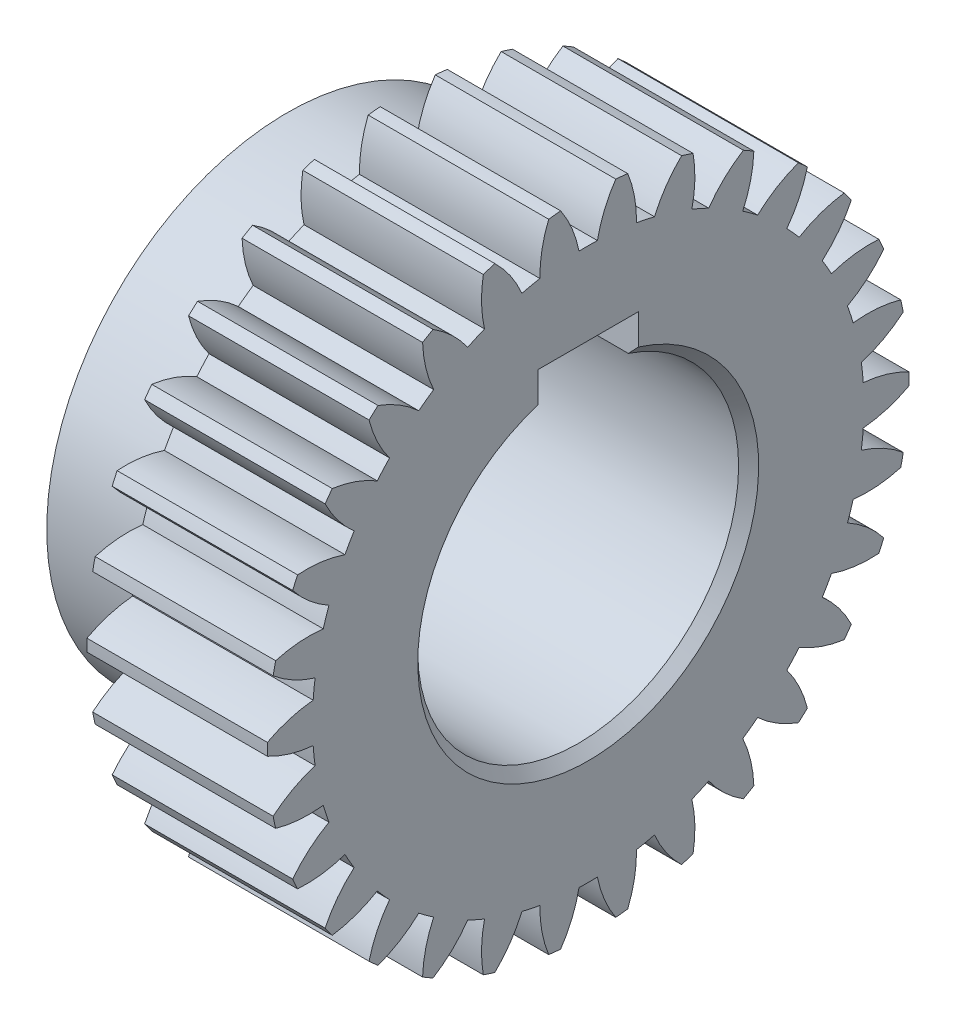
SolidWorks part; units mm, degrees
ref_plane "Plane1" through (0, 0, 0) normal (0, 0, 1) x (1, 0, 0)
ref_plane "Plane2" through (0, 0, 0) normal (0, 1, 0) x (1, 0, 0)
ref_plane "Plane3" through (0, 0, 0) normal (1, 0, 0) x (0, 0, -1)
sketch "HoldingSke" plane through (0, 0, 0) normal (0, 1, 0) x (1, 0, 0)
  line L0 (0, 0) -> (0.433, -0.25)
  line L1 (-15, 0) -> (100, 0) construction
  line L2 (0, 0) -> (-2.1039, 2.3779)
  line L3 (0, 0) -> (-11.863, 4.5341)
  line L4 (0, 0) -> (7.479, 4.318)
  line L5 (0, 0) -> (-28.1086, -10.4837)
  line L6 (0, 0) -> (-14.9213, -10.0675)
  line L7 (-2.1039, 2.3779) -> (4.3536, 31.6747)
  line L8 (-76.2, 54.61) -> (-72.9, 54.61)
  line L9 (-71.009, 38.7566) -> (-53.1078, 45.2721)
  line L10 (-76.2, 71.12) -> (104.1128, 71.12)
  line L11 (0, 0) -> (-18, 0)
  line L12 (-76.2, 101.6) -> (-76.133, 101.6)
  line L13 (24.9733, 27.94) -> (52.9518, 28.4284)
  line L14 (24.9733, 27.94) -> (24.9743, 27.94)
  line L15 (24.9733, 27.94) -> (100.4006, 29.5858)
  line L16 (-63.627, -2) -> (-12.827, -2)
  circle A0 centre (0, 0) radius 16
  circle A1 centre (0, 0) radius 24
  circle A2 centre (0, 0) radius 24
  circle A3 centre (0, 0) radius 16
  dimension "MHD" = 48
  dimension "Hub_dia" = 48
  dimension "Bore" = 32
  dimension "MBD" = 32
  dimension "Num_teeth" = 30
  dimension "Pitch" = 0.5
  dimension "Overall_len" = 30
  dimension "Show_teeth" = 30
  dimension "Thickness" = 18
  dimension "OAL" = 30.0001
  dimension "T_dim" = 3.3
  dimension "Ap" = 20
  dimension "H" = 19.05
  dimension "Pitch_radius" = 180.3128
  dimension "Width" = 18
  dimension "Backlash" = 0.067
  dimension "Addendum_fac" = 1
  dimension "Dedendum_fac" = 1.25
  dimension "Clearance_fac" = 0.25
  dimension "Dedendum_add" = 0.001
  dimension "Module" = 2
sketch "BasProSke" plane through (0, 0, 0) normal (0, 1, 0) x (1, 0, 0)
  line L0 (-10, 0) -> (60, 0) construction
  line L1 (0, 0) -> (0, 32)
  line L2 (0, 0) -> (18, 0)
  line L3 (18, 0) -> (18, 32)
  line L4 (18, 32) -> (0, 32)
  dimension "Thickness" = 18
  dimension "Diameter" = 64
revolve "Base-Revolve" add sketch "BasProSke" angle 360 about L0
sketch "TooCutSke" plane through (0, 0, 0) normal (1, 0, 0) x (0, 0, -1)
  line L1 (0, 0) -> (0, 107) construction
  line L2 (0, 0) -> (-1.6873, 29.9525) construction
  line L3 (0, 0) -> (-6.2643, 59.6013) construction
  line L4 (-1.6873, 29.9525) -> (-3.1322, 29.8007) construction
  arc A0 (0.9186, 27.4837) -> (-0.9186, 27.4837) centre (0, 0) ccw
  arc A1 (2.7618, 31.9061) -> (-2.7618, 31.9061) centre (0, 0) ccw
  circle A2 centre (0, 0) radius 30 construction
  circle A3 centre (0, 0) radius 28.1908 construction
  arc A4 (-0.9186, 27.4837) -> (-2.7618, 31.9061) centre (-12.6936, 25.1712) ccw
  arc A5 (2.7618, 31.9061) -> (0.9186, 27.4837) centre (12.6936, 25.1712) ccw
  dimension "Root_dia" = 54.998
  dimension "Overcut_dia" = 64.0508
  dimension "Pitch_dia" = 60
  dimension "Base_dia" = 56.3816
  dimension "Flank_rad" = 12
  dimension "Half_ang" = 6
  dimension "Half_CT" = 1.4528
extrude "ToothCut" cut sketch "TooCutSke" along normal through all
fillet "Breaks" [suppressed] radius 0.04
fillet "RootFillets" [suppressed] radius 0.501
pattern_circular "TeethCuts" count 30 over 360 about axis through (0, 0, 0) along (1, 0, 0) of "ToothCut", "RootFillets", "Breaks"
sketch "HubNeaOneSke" plane through (0, 0, 0) normal (-1, 0, 0) x (0, 0, 1)
  circle A0 centre (0, 0) radius 24
  dimension "Diameter" = 48
extrude "HubNearOne" add sketch "HubNeaOneSke" along normal blind 12.0001
sketch "HubNeaBotSke" plane through (0, 0, 0) normal (-1, 0, 0) x (0, 0, 1)
  circle A0 centre (0, 0) radius 24
  dimension "Diameter" = 48
extrude "HubNearBoth" [suppressed] add sketch "HubNeaBotSke" along normal blind 6
ref_plane "FarPln" through (18, 0, 0) normal (1, 0, 0) x (0, 0, -1)
sketch "HubFarSke" plane through (18, 0, 0) normal (1, 0, 0) x (0, 0, -1)
  circle A0 centre (0, 0) radius 24
  dimension "Diameter" = 48
extrude "HubFar" [suppressed] add sketch "HubFarSke" along normal blind 6
sketch "BorSke" plane through (0, 0, 0) normal (1, 0, 0) x (0, 0, -1)
  circle A0 centre (0, 0) radius 16
  dimension "Diameter" = 32
extrude "Bore" cut sketch "BorSke" along normal mid plane 60.0001
sketch "KeySke" plane through (0, 0, 0) normal (1, 0, 0) x (0, 0, -1)
  line L0 (-5, 0) -> (-5, 19.3)
  line L1 (-5, 19.3) -> (5, 19.3)
  line L2 (5, 19.3) -> (5, 0)
  line L3 (0, 0) -> (0, 34) construction
  line L4 (-5, 0) -> (5, 0)
  dimension "Offset" = 19.3
  dimension "Width" = 10
extrude "Keyway" cut sketch "KeySke" along normal mid plane 60.0001
pattern_circular "Keyway2" [suppressed] count 2 every 90 about axis through (-10, 0, 0) along (1, 0, 0)
chamfer "Smusso1" distance 1 angle 45 1 edges at (18, -16, 0)
fillet "Raccordo1" radius 1 1 edges at (0, 0, -24)
equation "' \"Module@HoldingSke\" = 6.35"
equation "' \"Num_teeth@HoldingSke\" = 12"
equation "' \"Ap@HoldingSke\" =  20"
equation "' \"Ap@HoldingSke\" = 20"
equation "' \"Width@HoldingSke\" = 0.5 * 25.4"
equation "' \"Hub_dia@HoldingSke\"= 1 * 25.4"
equation "' \"Hub_dia@HoldingSke\" = 1 * 25.4"
equation "' \"Overall_len@HoldingSke\" = 1.0 * 25.4"
equation "' \"Bore@HoldingSke\" = 0.75 * 25.4"
equation "' \"T_dim@HoldingSke\" = 0.1 * 25.4"
equation "' \"Width@KeySke\" = 0.25 * 25.4"
equation "' \"Show_teeth@HoldingSke\" = 13"
equation "' \"Backlash@HoldingSke\" = 0.009 * 25.4"
equation "' \"Addendum_fac@HoldingSke\" = 1.0"
equation "' \"Dedendum_fac@HoldingSke\" = 1.25"
equation "' \"Dedendum_add@HoldingSke\" = 0.00005 * 25.4"
equation "' \"Clearance_fac@HoldingSke\" = 0.25"
equation "\"Pitch@HoldingSke\" = 1 / \"Module@HoldingSke\""
equation "\"Overcut_dia@TooCutSke\" = (\"Num_teeth@HoldingSke\" + 2 * \"Addendum_fac@HoldingSke\") / \"Pitch@HoldingSke\" + 0.002 * 25.4"
equation "\"Pitch_dia@TooCutSke\" = \"Num_teeth@HoldingSke\" / \"Pitch@HoldingSke\""
equation "\"Base_dia@TooCutSke\" = \"Num_teeth@HoldingSke\" / \"Pitch@HoldingSke\" * cos((\"Ap@HoldingSke\"  * 3.14159265 / 180))"
equation "\"Root_dia@TooCutSke\" = (\"Num_teeth@HoldingSke\" + 2) / \"Pitch@HoldingSke\" - 2 * (\"Addendum_fac@HoldingSke\" + \"Dedendum_fac@HoldingSke\") / \"Pitch@HoldingSke\" - \"Dedendum_add@HoldingSke\" * 2"
equation "\"Half_ang@TooCutSke\" = 180 / \"Num_teeth@HoldingSke\""
equation "\"Half_CT@TooCutSke\" = \"Num_teeth@HoldingSke\" / \"Pitch@HoldingSke\" * sin((3.14159265 / 2 / \"Num_teeth@HoldingSke\")) / 2 - 7 * \"Backlash@HoldingSke\" / 4"
equation "\"Flank_rad@TooCutSke\" = \"Num_teeth@HoldingSke\" / \"Pitch@HoldingSke\" / 5"
equation "\"Radius@RootFillets\" = \"Clearance_fac@HoldingSke\" / \"Pitch@HoldingSke\" + \"Dedendum_add@HoldingSke\""
equation "\"Break_rad@Breaks\" = 0.02 / \"Pitch@HoldingSke\""
equation "\"Thickness@HoldingSke\" = \"Width@HoldingSke\""
equation "\"OAL@HoldingSke\" = \"Thickness@HoldingSke\""
equation "\"MHD@HoldingSke\" = (\"Num_teeth@HoldingSke\" + 2) / \"Pitch@HoldingSke\" - 2 * (\"Addendum_fac@HoldingSke\" + \"Dedendum_fac@HoldingSke\")  / \"Pitch@HoldingSke\" - \"Dedendum_add@HoldingSke\" * 2"
equation "\"MBD@HoldingSke\" = (\"Num_teeth@HoldingSke\" + 2) / \"Pitch@HoldingSke\" - 2 * (\"Addendum_fac@HoldingSke\" + \"Dedendum_fac@HoldingSke\")  / \"Pitch@HoldingSke\" - \"Dedendum_add@HoldingSke\" * 2 - 0.002 * 25.4"
equation "\"MHD@HoldingSke\" = ((sgn( \"MHD@HoldingSke\" - \"Hub_dia@HoldingSke\" )-1)*( \"MHD@HoldingSke\" - \"Hub_dia@HoldingSke\" ))/-2+ \"Hub_dia@HoldingSke\""
equation "\"MBD@HoldingSke\" = ((sgn( \"MBD@HoldingSke\" - \"Bore@HoldingSke\" )-1)*( \"MBD@HoldingSke\" - \"Bore@HoldingSke\" ))/-2+ \"Bore@HoldingSke\""
equation "\"OAL@HoldingSke\" = ((sgn( \"OAL@HoldingSke\" - \"Overall_len@HoldingSke\" )+1)*( \"OAL@HoldingSke\" - \"Overall_len@HoldingSke\" ))/2 + \"Overall_len@HoldingSke\" + 0.000002 * 25.4"
equation "\"Num_teeth@TeethCuts\" = int( \"Show_teeth@HoldingSke\" ) + 1"
equation "\"Num_teeth@TeethCuts\" = ((sgn( \"Num_teeth@TeethCuts\" - \"Num_teeth@HoldingSke\" )-1)*( \"Num_teeth@TeethCuts\" - \"Num_teeth@HoldingSke\" ))/-2+ \"Num_teeth@HoldingSke\""
equation "\"Num_teeth@TeethCuts\" = ((sgn( \"Num_teeth@TeethCuts\" - 2.0)+1)*( \"Num_teeth@TeethCuts\" - 2.0))/2 +2.0"
equation "\"Angle@TeethCuts\" = 360.0 / \"Num_teeth@HoldingSke\""
equation "\"Diameter@BasProSke\" = (\"Num_teeth@HoldingSke\" + 2 * \"Addendum_fac@HoldingSke\") / \"Pitch@HoldingSke\""
equation "\"Thickness@BasProSke\"  = \"Thickness@HoldingSke\""
equation "' \"Fillet_rad@BasProSke\" =  \"Thickness@HoldingSke\" * 0.05"
equation "' \"Fillet_rad@BasProSke\" = \"Thickness@HoldingSke\" * 0.05"
equation "\"MHD@HoldingSke\" = ((sgn( \"MHD@HoldingSke\" - \"Root_dia@TooCutSke\" )-1)*( \"MHD@HoldingSke\" - \"Root_dia@TooCutSke\" ))/-2+ \"Root_dia@TooCutSke\""
equation "\"Diameter@HubNeaOneSke\" = \"MHD@HoldingSke\""
equation "\"Length@HubNearOne\" = \"OAL@HoldingSke\" - \"Thickness@BasProSke\""
equation "\"Diameter@HubNeaBotSke\" = \"MHD@HoldingSke\""
equation "\"Length@HubNearBoth\" = ( \"OAL@HoldingSke\" - \"Thickness@BasProSke\" ) / 2.0"
equation "\"Thickness@FarPln\" = \"Thickness@BasProSke\""
equation "\"Diameter@HubFarSke\" = \"MHD@HoldingSke\""
equation "\"Length@HubFar\" = ( \"OAL@HoldingSke\" - \"Thickness@BasProSke\" ) / 2.0"
equation "\"D1@Keyway\" = \"OAL@HoldingSke\" * 2.0"
equation "\"Offset@KeySke\" = \"T_dim@HoldingSke\" + \"MBD@HoldingSke\" / 2.0"
